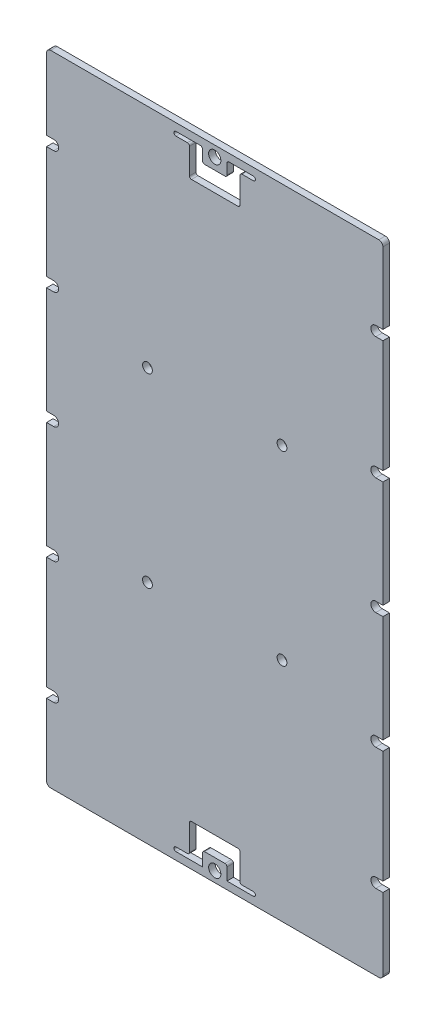
SolidWorks part; units mm, degrees
material "FR4_stuffedProtoboard"
ref_plane "Front Plane" through (0, 0, 0) normal (0, 0, 1) x (1, 0, 0)
ref_plane "Top Plane" through (0, 0, 0) normal (0, 1, 0) x (1, 0, 0)
ref_plane "Right Plane" through (0, 0, 0) normal (1, 0, 0) x (0, 0, -1)
sketch "Sketch1" plane through (0, 0, 0) normal (0, 0, 1) x (1, 0, 0)
  line L0 (-37, -67) -> (37, -67) construction
  line L5 (-37, 72.1) -> (-37, -72.1) construction
  line L6 (37, -72.1) -> (37, 72.1) construction
  line L7 (37, -68.6) -> (-37, -68.6) construction
  line L8 (-34.5, -74.6) -> (-4.5, -74.6) construction
  line L14 (-41.5, 81.1) -> (-41.5, 69.2) construction
  line L15 (-37, -57) -> (37, -57) construction
  line L18 (-41.5, 78.6) -> (41.5, 78.6)
  line L20 (-41.5, 78.6) -> (-41.5, -78.6)
  line L21 (-41.5, -78.6) -> (41.5, -78.6)
  line L22 (41.5, 78.6) -> (41.5, -78.6)
  line L23 (41.5, -81.1) -> (41.5, -69.2) construction
  line L24 (-39, -78.6) -> (39, -78.6) construction
  line L25 (-26.7, 78.6) -> (-28.3, 78.6) construction
  line L26 (37, -58.6) -> (-37, -58.6) construction
  line L27 (-37, -47) -> (37, -47) construction
  line L28 (37, -48.6) -> (-37, -48.6) construction
  line L29 (-37, -37) -> (37, -37) construction
  line L30 (37, -38.6) -> (-37, -38.6) construction
  line L31 (-37, -27) -> (37, -27) construction
  line L32 (37, -28.6) -> (-37, -28.6) construction
  line L33 (-37, -17) -> (37, -17) construction
  line L34 (37, -18.6) -> (-37, -18.6) construction
  line L35 (-37, -7) -> (37, -7) construction
  line L36 (37, -8.6) -> (-37, -8.6) construction
  line L37 (-37, -67) -> (-37, -57) construction
  line L38 (-37, 68.6) -> (37, 68.6) construction
  line L39 (37, 67) -> (-37, 67) construction
  line L40 (-4.5, 74.6) -> (-34.5, 74.6) construction
  line L41 (-37, 58.6) -> (37, 58.6) construction
  line L46 (37, 57) -> (-37, 57) construction
  line L47 (-37, 48.6) -> (37, 48.6) construction
  line L48 (37, 47) -> (-37, 47) construction
  line L49 (-37, 38.6) -> (37, 38.6) construction
  line L50 (37, 37) -> (-37, 37) construction
  line L51 (-37, 28.6) -> (37, 28.6) construction
  line L52 (37, 27) -> (-37, 27) construction
  line L53 (-37, 18.6) -> (37, 18.6) construction
  line L55 (-41.25, 78.35) -> (41.25, 78.35)
  line L56 (-41.25, 78.35) -> (-41.25, -78.35)
  line L57 (-41.25, -78.35) -> (41.25, -78.35)
  line L58 (41.25, 78.35) -> (41.25, -78.35)
  line L59 (37, 17) -> (-37, 17) construction
  line L60 (-37, 68.6) -> (-37, 58.6) construction
  line L61 (-34.5, 74.6) -> (-4.5, 74.6)
  line L63 (-37, 72.1) -> (-37, -72.1)
  line L64 (-34.5, -74.6) -> (-4.5, -74.6)
  line L66 (-2.5, -73.6) -> (2.5, -73.6)
  line L67 (2.5, -73.6) -> (-2.5, -73.6) construction
  line L69 (4.5, -74.6) -> (34.5, -74.6)
  line L70 (4.5, -74.6) -> (34.5, -74.6) construction
  line L75 (4.5, -74.6) -> (26.5, -74.6) construction
  line L76 (37, -72.1) -> (37, 72.1)
  line L77 (34.5, 74.6) -> (4.5, 74.6)
  line L78 (34.5, 74.6) -> (4.5, 74.6) construction
  line L79 (-2.5, 73.6) -> (2.5, 73.6)
  circle A24 centre (-39.5, 58.6) radius 0.8
  circle A25 centre (-39.5, 28.6) radius 0.8
  circle A26 centre (-39.5, 0) radius 0.8
  circle A27 centre (-39.5, -28.6) radius 0.8
  circle A28 centre (-39.5, -58.6) radius 0.8
  circle A29 centre (0, -75.8) radius 1.5
  circle A30 centre (39.5, -58.6) radius 0.8
  circle A31 centre (39.5, -28.6) radius 0.8
  circle A32 centre (39.5, 0) radius 0.8
  circle A33 centre (39.5, 28.6) radius 0.8
  circle A34 centre (39.5, 58.6) radius 0.8
  circle A35 centre (-39.5, 58.6) radius 0.8 construction
  circle A36 centre (-16.5, 22.8) radius 0.8
  circle A37 centre (-16.5, -22.8) radius 0.8
  circle A38 centre (16.5, -22.8) radius 0.8
  circle A39 centre (16.5, 22.8) radius 0.8
  circle A40 centre (0, 75.8) radius 1.5
  circle A41 centre (0, 75.8) radius 1.5 construction
  arc A42 (2.5, -73.6) -> (4.5, -74.6) centre (4.5, -72.1) ccw construction
  arc A43 (37, 72.1) -> (34.5, 74.6) centre (34.5, 72.1) ccw
  arc A44 (-34.5, 74.6) -> (-37, 72.1) centre (-34.5, 72.1) ccw
  circle A45 centre (0, -75.8) radius 1.5 construction
  arc A46 (34.5, -74.6) -> (37, -72.1) centre (34.5, -72.1) ccw
  arc A47 (-37, -72.1) -> (-34.5, -74.6) centre (-34.5, -72.1) ccw
  arc A48 (-4.5, 74.6) -> (-2.5, 73.6) centre (-4.5, 72.1) cw
  arc A49 (4.5, 74.6) -> (2.5, 73.6) centre (4.5, 72.1) ccw
  arc A50 (-4.5, -74.6) -> (-2.5, -73.6) centre (-4.5, -72.1) ccw construction
  arc A51 (-4.5, -74.6) -> (-2.5, -73.6) centre (-4.5, -72.1) ccw
  arc A52 (4.5, -74.6) -> (2.5, -73.6) centre (4.5, -72.1) cw
  point P167 (-37, 74.6)
  point P198 (37, -74.6)
  dimension "D2" = 7
  dimension "D8" = 2.5
  dimension "D1" = 1.6
  dimension "D3" = 10
  dimension "D4" = 1.6
  dimension "D5" = 6
  dimension "D6" = 6
  dimension "D10" = 0.25
  dimension "6" = 6
  dimension "D7" = 10
  dimension "D9" = 0.25
  dimension "D11" = 0.25
  dimension "D12" = 0.25
extrude "Base shape" add sketch "Sketch1" along normal blind 1.6
sketch "Connector locations" plane through (0, 0, 0) normal (0, 0, -1) x (-1, 0, 0)
  line L0 (41.25, 78.35) -> (41.25, -78.35) construction
  line L1 (-12.32, -54.84) -> (12.32, -54.84)
  line L2 (-12.32, -54.84) -> (-12.32, -53.44)
  line L3 (-12.32, -53.44) -> (12.32, -53.44)
  line L4 (12.32, -54.84) -> (12.32, -53.44)
  line L5 (-12.32, -54.84) -> (12.32, -53.44) construction
  line L6 (-12.32, -53.44) -> (12.32, -54.84) construction
  line L7 (22.08, -54.84) -> (33.92, -54.84)
  line L8 (22.08, -54.84) -> (22.08, -53.44)
  line L9 (22.08, -53.44) -> (33.92, -53.44)
  line L10 (33.92, -54.84) -> (33.92, -53.44)
  line L11 (22.08, -54.84) -> (33.92, -53.44) construction
  line L12 (22.08, -53.44) -> (33.92, -54.84) construction
  line L13 (9.28, -64.84) -> (33.92, -64.84)
  line L14 (9.28, -64.84) -> (9.28, -63.44)
  line L15 (9.28, -63.44) -> (33.92, -63.44)
  line L16 (33.92, -64.84) -> (33.92, -63.44)
  line L17 (9.28, -64.84) -> (33.92, -63.44) construction
  line L18 (9.28, -63.44) -> (33.92, -64.84) construction
  line L19 (33.92, 52.16) -> (33.92, 50.76)
  line L22 (-41.25, -54.14) -> (41.25, -54.14) construction
  line L23 (22.08, -44.84) -> (33.92, -44.84)
  line L24 (22.08, -44.84) -> (22.08, -43.44)
  line L25 (22.08, -43.44) -> (33.92, -43.44)
  line L26 (33.92, -44.84) -> (33.92, -43.44)
  line L27 (22.08, -43.44) -> (33.92, -44.84) construction
  line L28 (22.08, -44.84) -> (33.92, -43.44) construction
  line L29 (12.32, -44.84) -> (12.32, -43.44)
  line L30 (-12.32, -44.84) -> (12.32, -44.84)
  line L31 (-12.32, -43.44) -> (12.32, -44.84) construction
  line L32 (-12.32, -44.84) -> (12.32, -43.44) construction
  line L33 (-12.32, -43.44) -> (12.32, -43.44)
  line L34 (-12.32, -44.84) -> (-12.32, -43.44)
  line L35 (22.08, -34.84) -> (33.92, -34.84)
  line L36 (22.08, -34.84) -> (22.08, -33.44)
  line L37 (22.08, -33.44) -> (33.92, -33.44)
  line L38 (33.92, -34.84) -> (33.92, -33.44)
  line L39 (22.08, -33.44) -> (33.92, -34.84) construction
  line L40 (22.08, -34.84) -> (33.92, -33.44) construction
  line L41 (12.32, -34.84) -> (12.32, -33.44)
  line L42 (-12.32, -34.84) -> (12.32, -34.84)
  line L43 (-12.32, -33.44) -> (12.32, -34.84) construction
  line L44 (-12.32, -34.84) -> (12.32, -33.44) construction
  line L45 (-12.32, -33.44) -> (12.32, -33.44)
  line L46 (-12.32, -34.84) -> (-12.32, -33.44)
  line L47 (22.08, -24.84) -> (33.92, -24.84)
  line L48 (22.08, -24.84) -> (22.08, -23.44)
  line L49 (22.08, -23.44) -> (33.92, -23.44)
  line L50 (33.92, -24.84) -> (33.92, -23.44)
  line L51 (22.08, -23.44) -> (33.92, -24.84) construction
  line L52 (22.08, -24.84) -> (33.92, -23.44) construction
  line L53 (12.32, -24.84) -> (12.32, -23.44)
  line L54 (-12.32, -24.84) -> (12.32, -24.84)
  line L55 (-12.32, -23.44) -> (12.32, -24.84) construction
  line L56 (-12.32, -24.84) -> (12.32, -23.44) construction
  line L57 (-12.32, -23.44) -> (12.32, -23.44)
  line L58 (-12.32, -24.84) -> (-12.32, -23.44)
  line L59 (22.08, -14.84) -> (33.92, -14.84)
  line L60 (22.08, -14.84) -> (22.08, -13.44)
  line L61 (22.08, -13.44) -> (33.92, -13.44)
  line L62 (33.92, -14.84) -> (33.92, -13.44)
  line L63 (22.08, -13.44) -> (33.92, -14.84) construction
  line L64 (22.08, -14.84) -> (33.92, -13.44) construction
  line L65 (12.32, -14.84) -> (12.32, -13.44)
  line L66 (-12.32, -14.84) -> (12.32, -14.84)
  line L67 (-12.32, -13.44) -> (12.32, -14.84) construction
  line L68 (-12.32, -14.84) -> (12.32, -13.44) construction
  line L69 (-12.32, -13.44) -> (12.32, -13.44)
  line L70 (-12.32, -14.84) -> (-12.32, -13.44)
  line L71 (22.08, -4.84) -> (33.92, -4.84)
  line L72 (22.08, -4.84) -> (22.08, -3.44)
  line L73 (22.08, -3.44) -> (33.92, -3.44)
  line L74 (33.92, -4.84) -> (33.92, -3.44)
  line L75 (22.08, -3.44) -> (33.92, -4.84) construction
  line L76 (22.08, -4.84) -> (33.92, -3.44) construction
  line L77 (12.32, -4.84) -> (12.32, -3.44)
  line L78 (-12.32, -4.84) -> (12.32, -4.84)
  line L79 (-12.32, -3.44) -> (12.32, -4.84) construction
  line L80 (-12.32, -4.84) -> (12.32, -3.44) construction
  line L81 (-12.32, -3.44) -> (12.32, -3.44)
  line L82 (-12.32, -4.84) -> (-12.32, -3.44)
  line L87 (41.25, -78.35) -> (-41.25, -78.35) construction
  line L88 (37, 72.1) -> (37, -72.1) construction
  line L91 (-37, -72.1) -> (-37, 72.1) construction
  line L92 (37, -67) -> (-37, -67) construction
  line L99 (37, 58.6) -> (-37, 58.6) construction
  line L100 (37, 68.6) -> (-37, 68.6) construction
  line L103 (-41.25, 78.35) -> (-41.25, -78.35) construction
  line L107 (28, -54.14) -> (28, -44.14) construction
  line L108 (33.92, 52.16) -> (22.08, 52.16)
  line L109 (33.92, 62.16) -> (22.08, 62.16)
  line L110 (33.92, 62.16) -> (33.92, 60.76)
  line L111 (33.92, 60.76) -> (22.08, 60.76)
  line L112 (22.08, 62.16) -> (22.08, 60.76)
  line L113 (33.92, 62.16) -> (22.08, 60.76) construction
  line L114 (33.92, 60.76) -> (22.08, 62.16) construction
  line L115 (12.32, 62.16) -> (-12.32, 62.16)
  line L116 (12.32, 62.16) -> (12.32, 60.76)
  line L117 (12.32, 60.76) -> (-12.32, 60.76)
  line L118 (-12.32, 62.16) -> (-12.32, 60.76)
  line L119 (12.32, 62.16) -> (-12.32, 60.76) construction
  line L120 (12.32, 60.76) -> (-12.32, 62.16) construction
  line L121 (33.92, 72.16) -> (9.28, 72.16)
  line L122 (33.92, 72.16) -> (33.92, 70.76)
  line L123 (33.92, 70.76) -> (9.28, 70.76)
  line L124 (9.28, 72.16) -> (9.28, 70.76)
  line L125 (33.92, 72.16) -> (9.28, 70.76) construction
  line L126 (33.92, 70.76) -> (9.28, 72.16) construction
  line L128 (33.92, 50.76) -> (22.08, 50.76)
  line L129 (33.92, 50.76) -> (22.08, 52.16) construction
  line L130 (33.92, 52.16) -> (22.08, 50.76) construction
  line L131 (22.08, 52.16) -> (22.08, 50.76)
  line L132 (12.32, 50.76) -> (-12.32, 52.16) construction
  line L133 (12.32, 50.76) -> (-12.32, 50.76)
  line L134 (12.32, 52.16) -> (-12.32, 50.76) construction
  line L135 (12.32, 52.16) -> (-12.32, 52.16)
  line L136 (-12.32, 52.16) -> (-12.32, 50.76)
  line L137 (12.32, 52.16) -> (12.32, 50.76)
  line L138 (33.92, 42.16) -> (33.92, 40.76)
  line L139 (33.92, 42.16) -> (22.08, 42.16)
  line L140 (33.92, 40.76) -> (22.08, 40.76)
  line L141 (33.92, 40.76) -> (22.08, 42.16) construction
  line L142 (33.92, 42.16) -> (22.08, 40.76) construction
  line L143 (22.08, 42.16) -> (22.08, 40.76)
  line L144 (12.32, 40.76) -> (-12.32, 42.16) construction
  line L145 (12.32, 40.76) -> (-12.32, 40.76)
  line L146 (12.32, 42.16) -> (-12.32, 40.76) construction
  line L147 (12.32, 42.16) -> (-12.32, 42.16)
  line L148 (-12.32, 42.16) -> (-12.32, 40.76)
  line L149 (12.32, 42.16) -> (12.32, 40.76)
  line L150 (28, 61.46) -> (28, 51.46) construction
  line L151 (-32.9146, -65.7346) -> (-35.0854, -67.9054) construction
  line L152 (-35.0854, -65.7346) -> (-32.9146, -67.9054) construction
  line L155 (-35.0854, -65.7346) -> (-35.0854, -67.9054) construction
  line L156 (-29.0854, -65.7346) -> (-26.9146, -67.9054) construction
  line L157 (-26.9146, -65.7346) -> (-29.0854, -67.9054) construction
  line L158 (-23.0854, -65.7346) -> (-20.9146, -67.9054) construction
  line L159 (-20.9146, -65.7346) -> (-23.0854, -67.9054) construction
  line L160 (-29.0854, -55.7346) -> (-26.9146, -57.9054) construction
  line L161 (-26.9146, -55.7346) -> (-29.0854, -57.9054) construction
  line L162 (-23.0854, -55.7346) -> (-20.9146, -57.9054) construction
  line L163 (-20.9146, -55.7346) -> (-23.0854, -57.9054) construction
  line L164 (-29.0854, -45.7346) -> (-26.9146, -47.9054) construction
  line L165 (-26.9146, -45.7346) -> (-29.0854, -47.9054) construction
  line L166 (-23.0854, -45.7346) -> (-20.9146, -47.9054) construction
  line L167 (-20.9146, -45.7346) -> (-23.0854, -47.9054) construction
  line L168 (-29.0854, -35.7346) -> (-26.9146, -37.9054) construction
  line L169 (-26.9146, -35.7346) -> (-29.0854, -37.9054) construction
  line L170 (-23.0854, -35.7346) -> (-20.9146, -37.9054) construction
  line L171 (-20.9146, -35.7346) -> (-23.0854, -37.9054) construction
  line L172 (-29.0854, -25.7346) -> (-26.9146, -27.9054) construction
  line L173 (-26.9146, -25.7346) -> (-29.0854, -27.9054) construction
  line L174 (-23.0854, -25.7346) -> (-20.9146, -27.9054) construction
  line L175 (-20.9146, -25.7346) -> (-23.0854, -27.9054) construction
  line L176 (-29.0854, -15.7346) -> (-26.9146, -17.9054) construction
  line L177 (-26.9146, -15.7346) -> (-29.0854, -17.9054) construction
  line L178 (-23.0854, -15.7346) -> (-20.9146, -17.9054) construction
  line L179 (-20.9146, -15.7346) -> (-23.0854, -17.9054) construction
  line L180 (-29.0854, -5.7346) -> (-26.9146, -7.9054) construction
  line L181 (-26.9146, -5.7346) -> (-29.0854, -7.9054) construction
  line L182 (-23.0854, -5.7346) -> (-20.9146, -7.9054) construction
  line L183 (-20.9146, -5.7346) -> (-23.0854, -7.9054) construction
  line L192 (-35.0854, -55.7346) -> (-32.9146, -57.9054) construction
  line L193 (-32.9146, -55.7346) -> (-35.0854, -57.9054) construction
  line L194 (-35.0854, -45.7346) -> (-32.9146, -47.9054) construction
  line L195 (-32.9146, -45.7346) -> (-35.0854, -47.9054) construction
  line L196 (-35.0854, -35.7346) -> (-32.9146, -37.9054) construction
  line L197 (-32.9146, -35.7346) -> (-35.0854, -37.9054) construction
  line L198 (-35.0854, -25.7346) -> (-32.9146, -27.9054) construction
  line L199 (-32.9146, -25.7346) -> (-35.0854, -27.9054) construction
  line L200 (-35.0854, -15.7346) -> (-32.9146, -17.9054) construction
  line L201 (-32.9146, -15.7346) -> (-35.0854, -17.9054) construction
  line L202 (-35.0854, -5.7346) -> (-32.9146, -7.9054) construction
  line L203 (-32.9146, -5.7346) -> (-35.0854, -7.9054) construction
  line L208 (-34, -66.82) -> (-28, -66.82) construction
  line L209 (-34, -66.82) -> (-34, -56.82) construction
  line L210 (-32.9146, 69.8654) -> (-35.0854, 67.6946) construction
  line L211 (-35.0854, 69.8654) -> (-32.9146, 67.6946) construction
  line L212 (-35.0854, 69.8654) -> (-35.0854, 67.6946) construction
  line L215 (-26.9146, 69.8654) -> (-29.0854, 67.6946) construction
  line L216 (-29.0854, 69.8654) -> (-26.9146, 67.6946) construction
  line L217 (-20.9146, 69.8654) -> (-23.0854, 67.6946) construction
  line L218 (-23.0854, 69.8654) -> (-20.9146, 67.6946) construction
  line L219 (-26.9146, 59.8654) -> (-29.0854, 57.6946) construction
  line L220 (-29.0854, 59.8654) -> (-26.9146, 57.6946) construction
  line L221 (-20.9146, 59.8654) -> (-23.0854, 57.6946) construction
  line L222 (-23.0854, 59.8654) -> (-20.9146, 57.6946) construction
  line L223 (-26.9146, 49.8654) -> (-29.0854, 47.6946) construction
  line L224 (-29.0854, 49.8654) -> (-26.9146, 47.6946) construction
  line L225 (-20.9146, 49.8654) -> (-23.0854, 47.6946) construction
  line L226 (-23.0854, 49.8654) -> (-20.9146, 47.6946) construction
  line L227 (-26.9146, 39.8654) -> (-29.0854, 37.6946) construction
  line L228 (-29.0854, 39.8654) -> (-26.9146, 37.6946) construction
  line L229 (-20.9146, 39.8654) -> (-23.0854, 37.6946) construction
  line L230 (-23.0854, 39.8654) -> (-20.9146, 37.6946) construction
  line L231 (-32.9146, 59.8654) -> (-35.0854, 57.6946) construction
  line L232 (-35.0854, 59.8654) -> (-32.9146, 57.6946) construction
  line L233 (-32.9146, 49.8654) -> (-35.0854, 47.6946) construction
  line L234 (-35.0854, 49.8654) -> (-32.9146, 47.6946) construction
  line L235 (-32.9146, 39.8654) -> (-35.0854, 37.6946) construction
  line L236 (-35.0854, 39.8654) -> (-32.9146, 37.6946) construction
  line L237 (-34, 68.78) -> (-28, 68.78) construction
  line L238 (-34, 68.78) -> (-34, 58.78) construction
  line L239 (-32.9146, 29.8654) -> (-35.0854, 27.6946) construction
  line L240 (-35.0854, 29.8654) -> (-32.9146, 27.6946) construction
  line L241 (-26.9146, 29.8654) -> (-29.0854, 27.6946) construction
  line L242 (-29.0854, 29.8654) -> (-26.9146, 27.6946) construction
  line L243 (-20.9146, 29.8654) -> (-23.0854, 27.6946) construction
  line L244 (-23.0854, 29.8654) -> (-20.9146, 27.6946) construction
  line L245 (-32.9146, 19.8654) -> (-35.0854, 17.6946) construction
  line L246 (-35.0854, 19.8654) -> (-32.9146, 17.6946) construction
  line L247 (-26.9146, 19.8654) -> (-29.0854, 17.6946) construction
  line L248 (-29.0854, 19.8654) -> (-26.9146, 17.6946) construction
  line L249 (-20.9146, 19.8654) -> (-23.0854, 17.6946) construction
  line L250 (-23.0854, 19.8654) -> (-20.9146, 17.6946) construction
  line L251 (33.92, 32.16) -> (33.92, 30.76)
  line L252 (33.92, 32.16) -> (22.08, 32.16)
  line L253 (33.92, 30.76) -> (22.08, 30.76)
  line L254 (33.92, 30.76) -> (22.08, 32.16) construction
  line L255 (33.92, 32.16) -> (22.08, 30.76) construction
  line L256 (22.08, 32.16) -> (22.08, 30.76)
  line L257 (12.32, 30.76) -> (-12.32, 32.16) construction
  line L258 (12.32, 30.76) -> (-12.32, 30.76)
  line L259 (12.32, 32.16) -> (-12.32, 30.76) construction
  line L260 (12.32, 32.16) -> (-12.32, 32.16)
  line L261 (-12.32, 32.16) -> (-12.32, 30.76)
  line L262 (12.32, 32.16) -> (12.32, 30.76)
  line L263 (33.92, 22.16) -> (33.92, 20.76)
  line L264 (33.92, 22.16) -> (22.08, 22.16)
  line L265 (33.92, 20.76) -> (22.08, 20.76)
  line L266 (33.92, 20.76) -> (22.08, 22.16) construction
  line L267 (33.92, 22.16) -> (22.08, 20.76) construction
  line L268 (22.08, 22.16) -> (22.08, 20.76)
  line L269 (12.32, 20.76) -> (-12.32, 22.16) construction
  line L270 (12.32, 20.76) -> (-12.32, 20.76)
  line L271 (12.32, 22.16) -> (-12.32, 20.76) construction
  line L272 (12.32, 22.16) -> (-12.32, 22.16)
  line L273 (-12.32, 22.16) -> (-12.32, 20.76)
  line L274 (12.32, 22.16) -> (12.32, 20.76)
  circle A0 centre (28, -54.14) radius 0.5
  circle A1 centre (0, -54.14) radius 0.5
  circle A2 centre (21.6, -64.14) radius 0.5
  circle A3 centre (28, -44.14) radius 0.5
  circle A4 centre (0, -44.14) radius 0.5
  circle A5 centre (28, -34.14) radius 0.5
  circle A6 centre (0, -34.14) radius 0.5
  circle A7 centre (28, -24.14) radius 0.5
  circle A8 centre (0, -24.14) radius 0.5
  circle A9 centre (28, -14.14) radius 0.5
  circle A10 centre (0, -14.14) radius 0.5
  circle A11 centre (28, -4.14) radius 0.5
  circle A12 centre (0, -4.14) radius 0.5
  circle A17 centre (0, 61.46) radius 0.5
  circle A18 centre (28, 61.46) radius 0.5
  circle A19 centre (21.6, 71.46) radius 0.5
  circle A20 centre (28, 51.46) radius 0.5
  circle A21 centre (0, 51.46) radius 0.5
  circle A22 centre (28, 41.46) radius 0.5
  circle A23 centre (0, 41.46) radius 0.5
  circle A24 centre (-32.9146, -65.7346) radius 0.32
  circle A25 centre (-35.0854, -65.7346) radius 0.32
  circle A26 centre (-35.0854, -67.9054) radius 0.32
  circle A27 centre (-32.9146, -67.9054) radius 0.32
  circle A28 centre (-26.9146, -65.7346) radius 0.32
  circle A29 centre (-29.0854, -67.9054) radius 0.32
  circle A30 centre (-29.0854, -65.7346) radius 0.32
  circle A31 centre (-26.9146, -67.9054) radius 0.32
  circle A32 centre (-20.9146, -65.7346) radius 0.32
  circle A33 centre (-23.0854, -67.9054) radius 0.32
  circle A34 centre (-23.0854, -65.7346) radius 0.32
  circle A35 centre (-20.9146, -67.9054) radius 0.32
  circle A36 centre (-26.9146, -55.7346) radius 0.32
  circle A37 centre (-29.0854, -57.9054) radius 0.32
  circle A38 centre (-29.0854, -55.7346) radius 0.32
  circle A39 centre (-26.9146, -57.9054) radius 0.32
  circle A40 centre (-20.9146, -55.7346) radius 0.32
  circle A41 centre (-23.0854, -57.9054) radius 0.32
  circle A42 centre (-23.0854, -55.7346) radius 0.32
  circle A43 centre (-20.9146, -57.9054) radius 0.32
  circle A44 centre (-26.9146, -45.7346) radius 0.32
  circle A45 centre (-29.0854, -47.9054) radius 0.32
  circle A46 centre (-29.0854, -45.7346) radius 0.32
  circle A47 centre (-26.9146, -47.9054) radius 0.32
  circle A48 centre (-20.9146, -45.7346) radius 0.32
  circle A49 centre (-23.0854, -47.9054) radius 0.32
  circle A50 centre (-23.0854, -45.7346) radius 0.32
  circle A51 centre (-20.9146, -47.9054) radius 0.32
  circle A52 centre (-26.9146, -35.7346) radius 0.32
  circle A53 centre (-29.0854, -37.9054) radius 0.32
  circle A54 centre (-29.0854, -35.7346) radius 0.32
  circle A55 centre (-26.9146, -37.9054) radius 0.32
  circle A56 centre (-20.9146, -35.7346) radius 0.32
  circle A57 centre (-23.0854, -37.9054) radius 0.32
  circle A58 centre (-23.0854, -35.7346) radius 0.32
  circle A59 centre (-20.9146, -37.9054) radius 0.32
  circle A60 centre (-26.9146, -25.7346) radius 0.32
  circle A61 centre (-29.0854, -27.9054) radius 0.32
  circle A62 centre (-29.0854, -25.7346) radius 0.32
  circle A63 centre (-26.9146, -27.9054) radius 0.32
  circle A64 centre (-20.9146, -25.7346) radius 0.32
  circle A65 centre (-23.0854, -27.9054) radius 0.32
  circle A66 centre (-23.0854, -25.7346) radius 0.32
  circle A67 centre (-20.9146, -27.9054) radius 0.32
  circle A68 centre (-26.9146, -15.7346) radius 0.32
  circle A69 centre (-29.0854, -17.9054) radius 0.32
  circle A70 centre (-29.0854, -15.7346) radius 0.32
  circle A71 centre (-26.9146, -17.9054) radius 0.32
  circle A72 centre (-20.9146, -15.7346) radius 0.32
  circle A73 centre (-23.0854, -17.9054) radius 0.32
  circle A74 centre (-23.0854, -15.7346) radius 0.32
  circle A75 centre (-20.9146, -17.9054) radius 0.32
  circle A76 centre (-26.9146, -5.7346) radius 0.32
  circle A77 centre (-29.0854, -7.9054) radius 0.32
  circle A78 centre (-29.0854, -5.7346) radius 0.32
  circle A79 centre (-26.9146, -7.9054) radius 0.32
  circle A80 centre (-20.9146, -5.7346) radius 0.32
  circle A81 centre (-23.0854, -7.9054) radius 0.32
  circle A82 centre (-23.0854, -5.7346) radius 0.32
  circle A83 centre (-20.9146, -7.9054) radius 0.32
  circle A100 centre (-32.9146, -55.7346) radius 0.32
  circle A101 centre (-35.0854, -57.9054) radius 0.32
  circle A102 centre (-35.0854, -55.7346) radius 0.32
  circle A103 centre (-32.9146, -57.9054) radius 0.32
  circle A104 centre (-32.9146, -45.7346) radius 0.32
  circle A105 centre (-35.0854, -47.9054) radius 0.32
  circle A106 centre (-35.0854, -45.7346) radius 0.32
  circle A107 centre (-32.9146, -47.9054) radius 0.32
  circle A108 centre (-32.9146, -35.7346) radius 0.32
  circle A109 centre (-35.0854, -37.9054) radius 0.32
  circle A110 centre (-35.0854, -35.7346) radius 0.32
  circle A111 centre (-32.9146, -37.9054) radius 0.32
  circle A112 centre (-32.9146, -25.7346) radius 0.32
  circle A113 centre (-35.0854, -27.9054) radius 0.32
  circle A114 centre (-35.0854, -25.7346) radius 0.32
  circle A115 centre (-32.9146, -27.9054) radius 0.32
  circle A116 centre (-32.9146, -15.7346) radius 0.32
  circle A117 centre (-35.0854, -17.9054) radius 0.32
  circle A118 centre (-35.0854, -15.7346) radius 0.32
  circle A119 centre (-32.9146, -17.9054) radius 0.32
  circle A120 centre (-32.9146, -5.7346) radius 0.32
  circle A121 centre (-35.0854, -7.9054) radius 0.32
  circle A122 centre (-35.0854, -5.7346) radius 0.32
  circle A123 centre (-32.9146, -7.9054) radius 0.32
  circle A132 centre (-32.9146, 69.8654) radius 0.32
  circle A133 centre (-35.0854, 69.8654) radius 0.32
  circle A134 centre (-35.0854, 67.6946) radius 0.32
  circle A135 centre (-32.9146, 67.6946) radius 0.32
  circle A136 centre (-26.9146, 69.8654) radius 0.32
  circle A137 centre (-29.0854, 69.8654) radius 0.32
  circle A138 centre (-29.0854, 67.6946) radius 0.32
  circle A139 centre (-26.9146, 67.6946) radius 0.32
  circle A140 centre (-20.9146, 69.8654) radius 0.32
  circle A141 centre (-23.0854, 69.8654) radius 0.32
  circle A142 centre (-23.0854, 67.6946) radius 0.32
  circle A143 centre (-20.9146, 67.6946) radius 0.32
  circle A144 centre (-26.9146, 59.8654) radius 0.32
  circle A145 centre (-29.0854, 59.8654) radius 0.32
  circle A146 centre (-29.0854, 57.6946) radius 0.32
  circle A147 centre (-26.9146, 57.6946) radius 0.32
  circle A148 centre (-20.9146, 59.8654) radius 0.32
  circle A149 centre (-23.0854, 59.8654) radius 0.32
  circle A150 centre (-23.0854, 57.6946) radius 0.32
  circle A151 centre (-20.9146, 57.6946) radius 0.32
  circle A152 centre (-26.9146, 49.8654) radius 0.32
  circle A153 centre (-29.0854, 49.8654) radius 0.32
  circle A154 centre (-29.0854, 47.6946) radius 0.32
  circle A155 centre (-26.9146, 47.6946) radius 0.32
  circle A156 centre (-20.9146, 49.8654) radius 0.32
  circle A157 centre (-23.0854, 49.8654) radius 0.32
  circle A158 centre (-23.0854, 47.6946) radius 0.32
  circle A159 centre (-20.9146, 47.6946) radius 0.32
  circle A160 centre (-26.9146, 39.8654) radius 0.32
  circle A161 centre (-29.0854, 39.8654) radius 0.32
  circle A162 centre (-29.0854, 37.6946) radius 0.32
  circle A163 centre (-26.9146, 37.6946) radius 0.32
  circle A164 centre (-20.9146, 39.8654) radius 0.32
  circle A165 centre (-23.0854, 39.8654) radius 0.32
  circle A166 centre (-23.0854, 37.6946) radius 0.32
  circle A167 centre (-20.9146, 37.6946) radius 0.32
  circle A168 centre (-32.9146, 59.8654) radius 0.32
  circle A169 centre (-35.0854, 59.8654) radius 0.32
  circle A170 centre (-35.0854, 57.6946) radius 0.32
  circle A171 centre (-32.9146, 57.6946) radius 0.32
  circle A172 centre (-32.9146, 49.8654) radius 0.32
  circle A173 centre (-35.0854, 49.8654) radius 0.32
  circle A174 centre (-35.0854, 47.6946) radius 0.32
  circle A175 centre (-32.9146, 47.6946) radius 0.32
  circle A176 centre (-32.9146, 39.8654) radius 0.32
  circle A177 centre (-35.0854, 39.8654) radius 0.32
  circle A178 centre (-35.0854, 37.6946) radius 0.32
  circle A179 centre (-32.9146, 37.6946) radius 0.32
  circle A180 centre (-32.9146, 29.8654) radius 0.32
  circle A181 centre (-35.0854, 29.8654) radius 0.32
  circle A182 centre (-35.0854, 27.6946) radius 0.32
  circle A183 centre (-32.9146, 27.6946) radius 0.32
  circle A184 centre (-26.9146, 29.8654) radius 0.32
  circle A185 centre (-29.0854, 29.8654) radius 0.32
  circle A186 centre (-29.0854, 27.6946) radius 0.32
  circle A187 centre (-26.9146, 27.6946) radius 0.32
  circle A188 centre (-20.9146, 29.8654) radius 0.32
  circle A189 centre (-23.0854, 29.8654) radius 0.32
  circle A190 centre (-23.0854, 27.6946) radius 0.32
  circle A191 centre (-20.9146, 27.6946) radius 0.32
  circle A192 centre (-32.9146, 19.8654) radius 0.32
  circle A193 centre (-35.0854, 19.8654) radius 0.32
  circle A194 centre (-35.0854, 17.6946) radius 0.32
  circle A195 centre (-32.9146, 17.6946) radius 0.32
  circle A196 centre (-26.9146, 19.8654) radius 0.32
  circle A197 centre (-29.0854, 19.8654) radius 0.32
  circle A198 centre (-29.0854, 17.6946) radius 0.32
  circle A199 centre (-26.9146, 17.6946) radius 0.32
  circle A200 centre (-20.9146, 19.8654) radius 0.32
  circle A201 centre (-23.0854, 19.8654) radius 0.32
  circle A202 centre (-23.0854, 17.6946) radius 0.32
  circle A203 centre (-20.9146, 17.6946) radius 0.32
  circle A204 centre (28, 31.46) radius 0.5
  circle A205 centre (0, 31.46) radius 0.5
  circle A206 centre (28, 21.46) radius 0.5
  circle A207 centre (0, 21.46) radius 0.5
  point P0 (0, -54.14)
  point P5 (28, -54.14)
  point P10 (21.6, -64.14)
  point P26 (28, 61.46)
  point P36 (28, -44.14)
  point P49 (28, -34.14)
  point P62 (28, -24.14)
  point P75 (28, -14.14)
  point P88 (28, -4.14)
  point P128 (0, 61.46)
  point P133 (21.6, 71.46)
  point P177 (-34, -66.82)
  point P193 (-28, -66.82)
  point P202 (-22, -66.82)
  point P211 (-28, -56.82)
  point P220 (-22, -56.82)
  point P229 (-28, -46.82)
  point P238 (-22, -46.82)
  point P247 (-28, -36.82)
  point P256 (-22, -36.82)
  point P265 (-28, -26.82)
  point P274 (-22, -26.82)
  point P283 (-28, -16.82)
  point P292 (-22, -16.82)
  point P301 (-28, -6.82)
  point P310 (-22, -6.82)
  point P355 (-34, -56.82)
  point P364 (-34, -46.82)
  point P373 (-34, -36.82)
  point P382 (-34, -26.82)
  point P391 (-34, -16.82)
  point P400 (-34, -6.82)
  point P427 (-34, 68.78)
  point P443 (-28, 68.78)
  point P452 (-22, 68.78)
  point P461 (-28, 58.78)
  point P470 (-22, 58.78)
  point P479 (-28, 48.78)
  point P488 (-22, 48.78)
  point P497 (-28, 38.78)
  point P506 (-22, 38.78)
  point P515 (-34, 58.78)
  point P524 (-34, 48.78)
  point P533 (-34, 38.78)
  point P542 (-34, 28.78)
  point P551 (-28, 28.78)
  point P560 (-22, 28.78)
  point P569 (-34, 18.78)
  point P578 (-28, 18.78)
  point P587 (-22, 18.78)
  dimension "D3" = 1
  dimension "D10" = 1
  dimension "D16" = 0.64
  dimension "D27" = 0.64
  dimension "D1" = 1.4
  dimension "D2" = 24.64
  dimension "D4" = 3.08
  dimension "D5" = 13.51
  dimension "D6" = 8.6
  dimension "D7" = 11.84
  dimension "D9" = 10
  dimension "D11" = 2.16
  dimension "D12" = 8.6
  dimension "D14" = 10
  dimension "D15" = 3.07
  dimension "D17" = 0.18
  dimension "D18" = 3
  dimension "D21" = 90
  dimension "D22" = 6
  dimension "D23" = 10
  dimension "D24" = 3.07
  dimension "D25" = 3
  dimension "D26" = 0.18
  dimension "D30" = 90
  dimension "D31" = 6
  dimension "D32" = 10
  dimension "D8" = 6
  dimension "D13" = 5
  dimension "D19" = 3
  dimension "D20" = 7
  dimension "D28" = 3
  dimension "D29" = 6
fillet "PCB corner fillets" radius 1 4 edges at (-41.25, -78.35, 0.8) (41.25, -78.35, 0.8) (-41.25, 78.35, 0.8) (41.25, 78.35, 0.8)
sketch "Sketch6" plane through (0, 0, 0) normal (0, 0, -1) x (-1, 0, 0)
  line L0 (9.5, 76.5) -> (3, 76.5)
  line L1 (3, 76.5) -> (3, 73)
  line L2 (3, 73) -> (-3, 73)
  line L3 (-3, 73) -> (-3, 76.5)
  line L4 (-3, 76.5) -> (-9.5, 76.5)
  line L5 (9.5, 75.5) -> (6.2, 75.5)
  line L6 (6.2, 75.5) -> (6.2, 68.2)
  line L7 (6.2, 68.2) -> (-6.2, 68.2)
  line L8 (-6.2, 68.2) -> (-6.2, 75.5)
  line L9 (-6.2, 75.5) -> (-9.5, 75.5)
  line L12 (3, 75.8) -> (0, 75.8) construction
  line L13 (0, 75.8) -> (-3, 75.8) construction
  line L14 (2.5, 73.6) -> (-2.5, 73.6) construction
  line L15 (-34.5, 74.6) -> (-4.5, 74.6) construction
  arc A0 (9.5, 76.5) -> (9.5, 75.5) centre (9.5, 76) cw
  arc A1 (-9.5, 76.5) -> (-9.5, 75.5) centre (-9.5, 76) ccw
  circle A2 centre (0, 75.8) radius 1.5
  dimension "D1" = 0.5
  dimension "D2" = 3
  dimension "D3" = 0.6
  dimension "D4" = 3
  dimension "D5" = 0.9
  dimension "D6" = 7.3
  dimension "D7" = 3.3
  dimension "D8" = 6.2
extrude "Solar connector cutout" cut sketch "Sketch6" against normal up to surface (1.6 mm away) up to face at (0, 0, 1.6)
mirror "Mirror solar cutout" about plane through (0, 0, 0) normal (0, 1, 0) of "Solar connector cutout"
fillet "Solar Hole fillets" radius 0.5 14 edges at (-6.2, 75.5, 0.8) (-6.2, 68.2, 0.8) (6.2, 68.2, 0.8) (3, 76.5, 0.8) (6.2, 75.5, 0.8) (3, 73, 0.8) (-3, 73, 0.8) (-3, 76.5, 0.8) (-3, -73, 0.8) (3, -73, 0.8) (6.2, -75.5, 0.8) (6.2, -68.2, 0.8) (-6.2, -68.2, 0.8) (-6.2, -75.5, 0.8)
hole_wizard "M2 Clearance Hole1" positions "3DSketch3" profile "Sketch9" hole size "M2" standard "ANSI Metric" end condition up to next
sketch3d "3DSketch3"
  point P64 (39.5, 58.6, 0)
  point P66 (39.5, 28.6, 0)
  point P68 (16.5, 22.8, 0)
  point P70 (-16.5, 22.8, 0)
  point P72 (-39.5, 28.6, 0)
  point P74 (-39.5, 58.6, 0)
  point P76 (-39.5, 0, 0)
  point P78 (39.5, 0, 0)
  point P80 (16.5, -22.8, 0)
  point P82 (-16.5, -22.8, 0)
  point P84 (-39.5, -28.6, 0)
  point P86 (39.5, -28.6, 0)
  point P88 (39.5, -58.6, 0)
  point P90 (-39.5, -58.6, 0)
sketch "Sketch9" plane through (39.5, 58.6, 0) normal (1, 0, 0) x (0, 1, 0)
  line L0 (0, 0) -> (0, 1.6)
  line L1 (0, 1.6) -> (1.2, 1.6)
  line L2 (1.2, 1.6) -> (1.2, 0)
  line L5 (1.2, 0) -> (0, 0)
  line L11 (0, -6.35) -> (0, 107.95) construction
  dimension "Thru Hole Dia." = 2.4
  dimension "Thru Hole Depth" = 1.6
sketch "Sketch10" plane through (0, 0, 0) normal (0, 0, -1) x (-1, 0, 0)
  line L43 (41.25, 78.35) -> (41.25, -78.35) construction
  line L44 (39.5, 59.8) -> (41.25, 59.8)
  line L45 (39.5, 59.8) -> (39.5, 57.4)
  line L46 (39.5, 57.4) -> (41.25, 57.4)
  line L47 (41.25, 59.8) -> (41.25, 57.4)
  line L48 (0, 0.88) -> (0, -0.88) construction
  line L49 (39.5, 29.8) -> (41.25, 29.8)
  line L50 (39.5, 29.8) -> (39.5, 27.4)
  line L51 (39.5, 27.4) -> (41.25, 27.4)
  line L52 (41.25, 29.8) -> (41.25, 27.4)
  line L53 (39.5, 1.2) -> (41.25, 1.2)
  line L54 (39.5, 1.2) -> (39.5, -1.2)
  line L55 (39.5, -1.2) -> (41.25, -1.2)
  line L56 (41.25, 1.2) -> (41.25, -1.2)
  line L57 (39.5, -27.4) -> (41.25, -27.4)
  line L58 (39.5, -27.4) -> (39.5, -29.8)
  line L59 (39.5, -29.8) -> (41.25, -29.8)
  line L60 (41.25, -27.4) -> (41.25, -29.8)
  line L61 (39.5, -57.4) -> (41.25, -57.4)
  line L62 (39.5, -57.4) -> (39.5, -59.8)
  line L63 (39.5, -59.8) -> (41.25, -59.8)
  line L64 (41.25, -57.4) -> (41.25, -59.8)
  line L65 (-41.25, -57.4) -> (-41.25, -59.8)
  line L66 (-39.5, -59.8) -> (-41.25, -59.8)
  line L67 (-39.5, -57.4) -> (-39.5, -59.8)
  line L68 (-39.5, -57.4) -> (-41.25, -57.4)
  line L69 (-41.25, -27.4) -> (-41.25, -29.8)
  line L70 (-39.5, -29.8) -> (-41.25, -29.8)
  line L71 (-39.5, -27.4) -> (-39.5, -29.8)
  line L72 (-39.5, -27.4) -> (-41.25, -27.4)
  line L73 (-41.25, 1.2) -> (-41.25, -1.2)
  line L74 (-39.5, -1.2) -> (-41.25, -1.2)
  line L75 (-39.5, 1.2) -> (-39.5, -1.2)
  line L76 (-39.5, 1.2) -> (-41.25, 1.2)
  line L77 (-41.25, 29.8) -> (-41.25, 27.4)
  line L78 (-39.5, 27.4) -> (-41.25, 27.4)
  line L79 (-39.5, 29.8) -> (-39.5, 27.4)
  line L80 (-39.5, 29.8) -> (-41.25, 29.8)
  line L81 (-41.25, 59.8) -> (-41.25, 57.4)
  line L82 (-39.5, 57.4) -> (-41.25, 57.4)
  line L83 (-39.5, 59.8) -> (-39.5, 57.4)
  line L84 (-39.5, 59.8) -> (-41.25, 59.8)
  circle A5 centre (39.5, 58.6) radius 1.2 construction
  circle A7 centre (39.5, 28.6) radius 1.2 construction
  circle A8 centre (39.5, 28.6) radius 1.2 construction
  circle A9 centre (39.5, 0) radius 1.2 construction
  circle A10 centre (39.5, -28.6) radius 1.2 construction
  circle A11 centre (39.5, -58.6) radius 1.2 construction
extrude "Screw Slots" cut sketch "Sketch10" against normal through all
sketch "Debug Slot" plane through (0, 0, 0) normal (0, 0, -1) x (-1, 0, 0)
  line L1 (29.5, 36.6) -> (35, 36.6)
  line L2 (27.5, 34.6) -> (27.5, 23)
  line L3 (29.5, 21) -> (35, 21)
  line L4 (37, 34.6) -> (37, 23)
  line L5 (41.25, 57.4) -> (41.25, 29.8) construction
  line L6 (40.25, 78.35) -> (-40.25, 78.35) construction
  line L16 (29.79, 22.68) -> (31.46, 22.68)
  line L17 (29.79, 22.68) -> (29.79, 34.51)
  line L18 (29.79, 34.51) -> (31.46, 34.51)
  line L19 (31.46, 22.68) -> (31.46, 34.51)
  line L20 (29.79, 22.68) -> (31.46, 34.51) construction
  line L21 (29.79, 34.51) -> (31.46, 22.68) construction
  arc A0 (27.5, 23) -> (29.5, 21) centre (29.5, 23) ccw
  arc A1 (35, 21) -> (37, 23) centre (35, 23) ccw
  arc A2 (35, 36.6) -> (37, 34.6) centre (35, 34.6) cw
  arc A3 (29.5, 36.6) -> (27.5, 34.6) centre (29.5, 34.6) ccw
  point P16 (0, 0)
  point P22 (30.625, 28.595)
  dimension "D5" = 2
  dimension "D1" = 15.6
  dimension "D2" = 9.5
  dimension "D3" = 4.25
  dimension "D4" = 41.75
  dimension "D6" = 2.09
  dimension "D11" = 1.67
  dimension "D12" = 11.83
  dimension "D13" = 2.29
